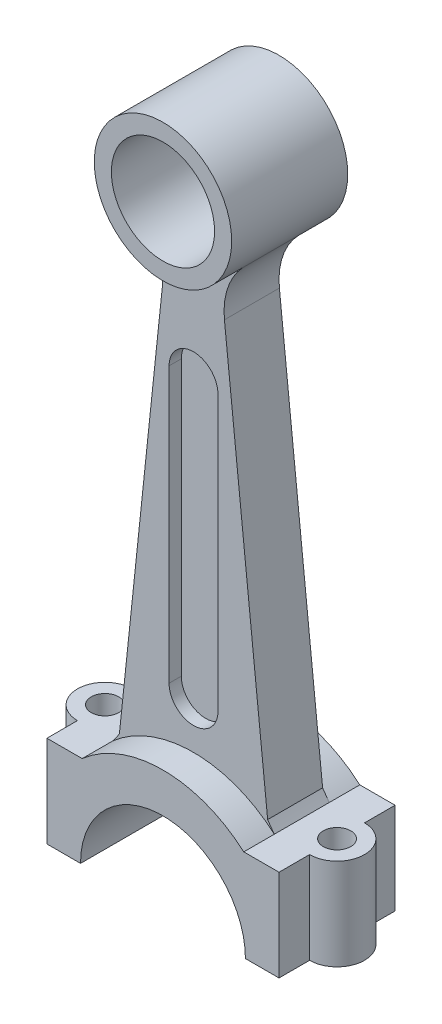
SolidWorks part; units mm, degrees
ref_plane "Front Plane" through (0, 0, 0) normal (0, 0, 1) x (1, 0, 0)
ref_plane "Top Plane" through (0, 0, 0) normal (0, 1, 0) x (1, 0, 0)
ref_plane "Right Plane" through (0, 0, 0) normal (1, 0, 0) x (0, 0, -1)
sketch "Sketch1" plane through (0, 0, 0) normal (0, 0, 1) x (1, 0, 0)
  line L1 (47, -69.3134) -> (47, -39.3134)
  line L2 (47, -39.3134) -> (26.4575, -39.3134)
  line L3 (47, -69.3134) -> (40, -69.3134)
  line L4 (24.2767, -36.2509) -> (10.1233, 98.4099)
  line L5 (40, -69.3134) -> (27, -69.3134)
  line L6 (0, -42.3134) -> (0, 163.0443) construction
  line L8 (-40, -69.3134) -> (-27, -69.3134)
  line L9 (-47, -69.3134) -> (-40, -69.3134)
  line L10 (-47, -69.3134) -> (-47, -39.3134)
  line L11 (-47, -39.3134) -> (-26.4575, -39.3134)
  line L12 (-24.2767, -36.2509) -> (-10.1233, 98.4099)
  circle A0 centre (0, 131.8866) radius 16.9
  arc A1 (16.25, 116.3242) -> (-16.25, 116.3242) centre (0, 131.8866) ccw
  arc A2 (27, -69.3134) -> (-27, -69.3134) centre (0, -69.3134) ccw
  arc A4 (16.25, 116.3242) -> (10.1233, 98.4099) centre (32.5, 100.7618) ccw
  arc A5 (26.4575, -39.3134) -> (24.2767, -36.2509) centre (106.81, 20.2137) cw
  arc A6 (-26.4575, -39.3134) -> (-24.2767, -36.2509) centre (-106.81, 20.2137) ccw
  arc A7 (-16.25, 116.3242) -> (-10.1233, 98.4099) centre (-32.5, 100.7618) cw
  dimension "D2" = 54
  dimension "D3" = 45
  dimension "D4" = 33.8
  dimension "D9" = 45
  dimension "D11" = 100
  dimension "D5" = 30
  dimension "D7" = 201.2
extrude "Boss-Extrude1" add sketch "Sketch1" along normal mid plane 38
sketch "Sketch2" plane through (0, -69.3134, 0) normal (0, -1, 0) x (1, 0, 0)
  line L0 (-47, 19) -> (-47, -19) construction
  line L1 (47, 19) -> (47, -19) construction
  line L2 (27, -19) -> (47, -19) construction
  line L3 (-38, 19) -> (38, 19)
  line L4 (-38, 19) -> (-38, 9)
  line L5 (-38, -19) -> (38, -19)
  line L6 (38, 19) -> (38, 9)
  line L7 (-38, 19) -> (38, -19) construction
  line L8 (-38, -19) -> (38, 19) construction
  line L9 (-38, -9) -> (-38, -19)
  line L10 (38, -9) -> (38, -19)
  line L11 (-51.3685, 22.7965) -> (51.3685, 22.7965)
  line L12 (-51.3685, 22.7965) -> (-51.3685, -22.7965)
  line L13 (-51.3685, -22.7965) -> (51.3685, -22.7965)
  line L14 (51.3685, 22.7965) -> (51.3685, -22.7965)
  line L15 (-51.3685, 22.7965) -> (51.3685, -22.7965) construction
  line L16 (-51.3685, -22.7965) -> (51.3685, 22.7965) construction
  circle A0 centre (38, 0) radius 4.5
  circle A1 centre (38, 0) radius 9
  circle A2 centre (-38, 0) radius 4.5
  circle A3 centre (-38, 0) radius 9
  point P13 (0, 0)
  point P19 (0, 0)
  dimension "D1" = 9
  dimension "D2" = 18
  dimension "D5" = 18
  dimension "D6" = 9
  dimension "D3" = 9
  dimension "D4" = 9
extrude "Cut-Extrude2" cut sketch "Sketch2" against normal blind 38 contours A2 | A0 | A1 L1 L2 L6 | A1 L10 L0 L1 | L14 L11 L12 L13 A3 L4 L3 L2 L1 L0 L5 L9
sketch "Sketch3" plane through (0, 0, 19) normal (0, 0, 1) x (1, 0, 0)
  line L0 (-26.4575, -39.3134) -> (-22.5, 131.8866)
  line L1 (22.5, 131.8866) -> (26.4575, -39.3134)
  arc A0 (-22.5, 131.8866) -> (22.5, 131.8866) centre (0, 131.8866) ccw
  arc A1 (26.4575, -39.3134) -> (-26.4575, -39.3134) centre (0, -69.3134) ccw
  dimension "D1" = 45
  dimension "80" = 80
extrude "Cut-Extrude3" cut sketch "Sketch3" against normal blind 10
mirror "Mirror1" about plane through (0, 0, 0) normal (0, 0, 1) of "Cut-Extrude3"
sketch "Sketch4" plane through (0, 0, 9) normal (0, 0, 1) x (1, 0, 0)
  line L0 (0, -19.944) -> (0, 94.8613) construction
  line L1 (0, 76.2866) -> (0, -13.7134) construction
  line L2 (8, 76.2866) -> (8, -13.7134)
  line L3 (-8, 76.2866) -> (-8, -13.7134)
  arc A0 (8, 76.2866) -> (-8, 76.2866) centre (0, 76.2866) ccw
  arc A1 (-8, -13.7134) -> (8, -13.7134) centre (0, -13.7134) ccw
  point P5 (0, 31.2866)
  dimension "D1" = 16
  dimension "D2" = 90
  dimension "D3" = 55.6
extrude "Cut-Extrude4" cut sketch "Sketch4" against normal blind 4
mirror "Mirror2" about plane through (0, 0, 0) normal (0, 0, 1) of "Cut-Extrude4"
